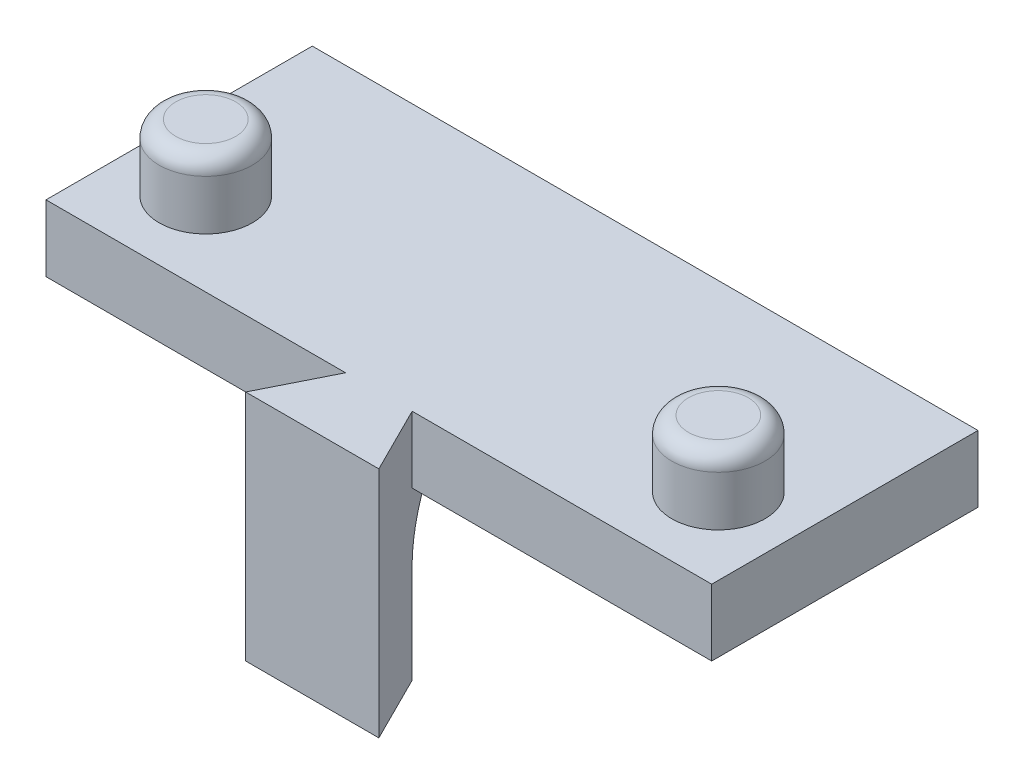
SolidWorks part; units mm, degrees
ref_plane "Front Plane" through (0, 0, 0) normal (0, 0, 1) x (1, 0, 0)
ref_plane "Top Plane" through (0, 0, 0) normal (0, 1, 0) x (1, 0, 0)
ref_plane "Right Plane" through (0, 0, 0) normal (1, 0, 0) x (0, 0, -1)
sketch "Sketch1" plane through (0, 0, 0) normal (0, 1, 0) x (1, 0, 0)
  line L0 (10, -8) -> (10, -10) construction
  line L1 (0, 0) -> (20, 0)
  line L2 (0, 0) -> (0, -8)
  line L4 (20, 0) -> (20, -8)
  line L5 (8, -10) -> (12, -10)
  line L9 (8, -10) -> (9, -8)
  line L10 (11, -8) -> (12, -10)
  line L11 (0, -8) -> (9, -8)
  line L12 (11, -8) -> (20, -8)
  point P10 (10, -10)
  point P13 (10, -9.424)
  dimension "D1" = 20
  dimension "D3" = 4
  dimension "D4" = 2
  dimension "D5" = 2
  dimension "D6" = 1
extrude "Boss-Extrude1" add sketch "Sketch1" along normal blind 2
sketch "Sketch2" plane through (0, 2, 0) normal (0, 1, 0) x (1, 0, 0)
  line L0 (10, 0) -> (10, -10) construction
  line L1 (20, 0) -> (0, 0) construction
  line L2 (8, -10) -> (12, -10) construction
  line L4 (0, -8) -> (9, -8) construction
  circle A0 centre (2.3, -5.5) radius 1.4
  circle A1 centre (17.7, -5.5) radius 1.4
  dimension "D1" = 7.7
  dimension "D2" = 2.5
extrude "Boss-Extrude2" add sketch "Sketch2" along normal blind 2
fillet "Fillet1" radius 0.5 2 edges at (2.3, 4, 6.9) (17.7, 4, 4.1)
sketch "Sketch3" plane through (0, 0, 0) normal (0, -1, 0) x (1, 0, 0)
  line L0 (8, 10) -> (12, 10)
  line L1 (12, 10) -> (11, 8)
  line L2 (11, 8) -> (9, 8)
  line L3 (9, 8) -> (8, 10)
extrude "Boss-Extrude3" add sketch "Sketch3" along normal blind 5
fillet "Fillet2" radius 2 1 edges at (10, 0, 8)
